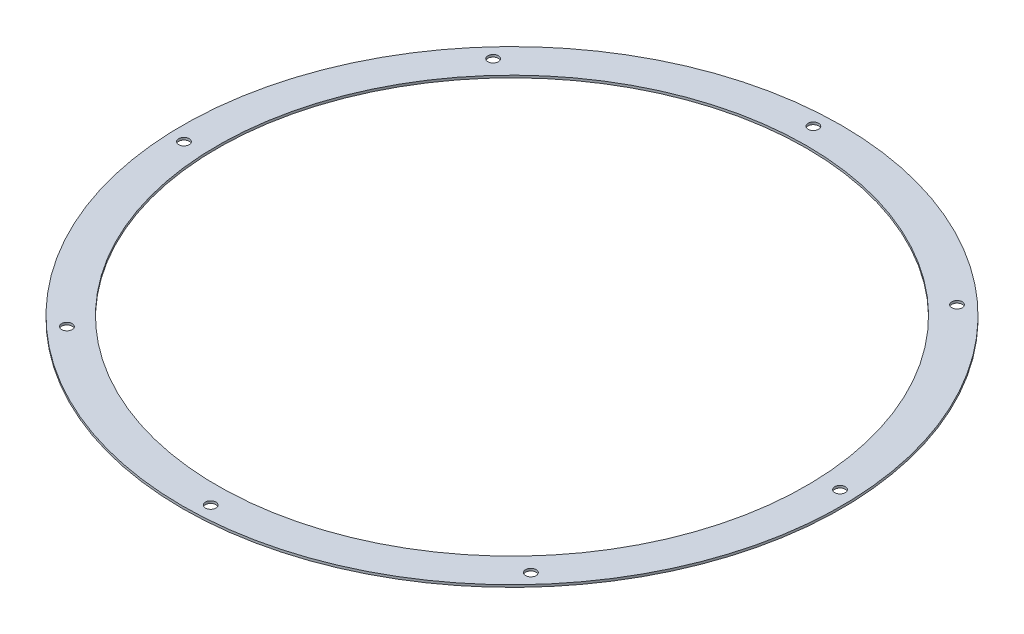
SolidWorks part; units mm, degrees
material "ASTM A36 Steel"
ref_plane "Front Plane" through (0, 0, 0) normal (0, 0, 1) x (1, 0, 0)
ref_plane "Top Plane" through (0, 0, 0) normal (0, 1, 0) x (1, 0, 0)
ref_plane "Right Plane" through (0, 0, 0) normal (1, 0, 0) x (0, 0, -1)
sketch "Sketch1" plane through (0, 0, 0) normal (0, 1, 0) x (1, 0, 0)
  circle A0 centre (0, 0) radius 282.5
  circle A1 centre (0, 0) radius 252.5
  dimension "D1" = 565
  dimension "D2" = 505
extrude "Boss-Extrude1" add sketch "Sketch1" along normal blind 2
sketch "Sketch2" plane through (0, 2, 0) normal (0, 1, 0) x (1, 0, 0)
  circle A0 centre (0, 0) radius 270 construction
  circle A1 centre (-11.4434, 269.7574) radius 4.5
  dimension "D1" = 540
  dimension "D2" = 9
extrude "Cut-Extrude1" cut sketch "Sketch2" against normal blind 5
pattern_circular "CirPattern1" count 8 every 45 about axis through (0, 0, 0) along (0, 1, 0) of "Cut-Extrude1"
